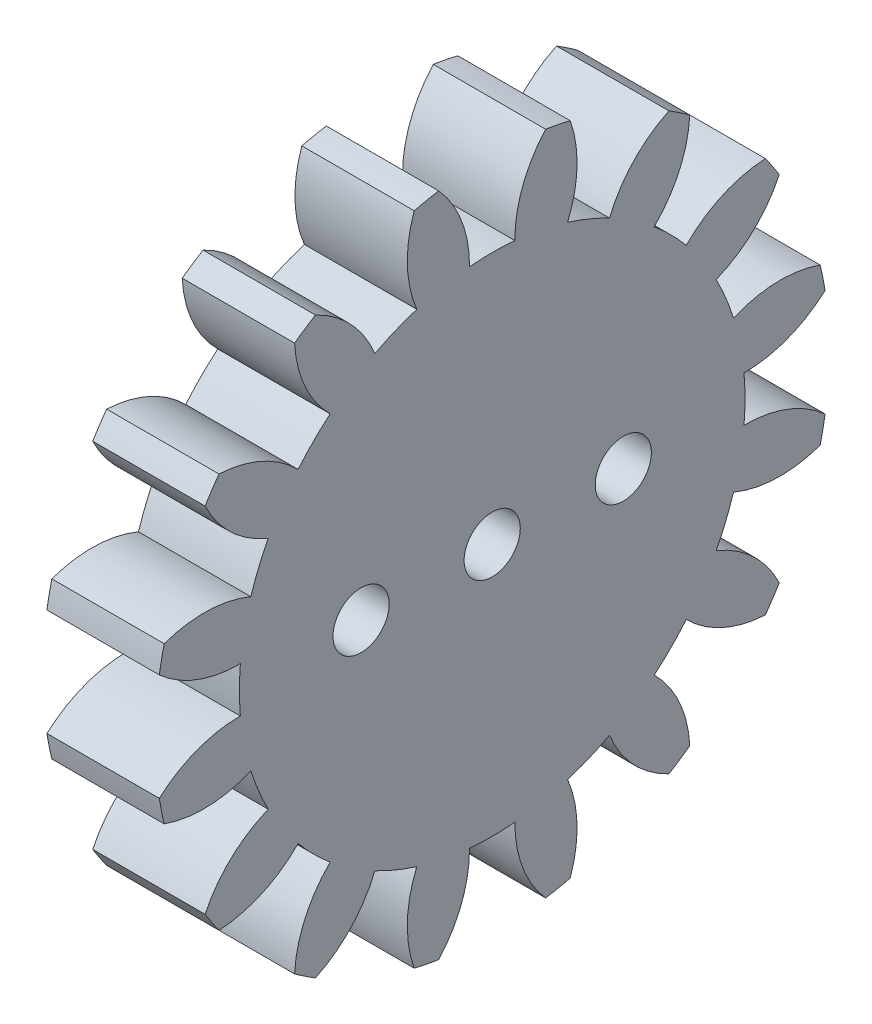
SolidWorks part; units mm, degrees
ref_plane "Plane1" through (0, 0, 0) normal (0, 0, 1) x (1, 0, 0)
ref_plane "Plane2" through (0, 0, 0) normal (0, 1, 0) x (1, 0, 0)
ref_plane "Plane3" through (0, 0, 0) normal (1, 0, 0) x (0, 0, -1)
sketch "HoldingSke" plane through (0, 0, 0) normal (0, 1, 0) x (1, 0, 0)
  line L0 (0, 0) -> (0.4806, -0.1378)
  line L1 (-15, 0) -> (100, 0) construction
  line L2 (0, 0) -> (-2.1039, 2.3779)
  line L3 (0, 0) -> (-11.863, 4.5341)
  line L4 (0, 0) -> (8.3015, 2.3804)
  line L5 (0, 0) -> (-46.8476, -17.4728)
  line L6 (0, 0) -> (-4.9738, -3.3558)
  line L7 (-2.1039, 2.3779) -> (8.6586, 51.2059)
  line L8 (-76.2, 54.61) -> (-74.8, 54.61)
  line L9 (-67.7845, 28.3722) -> (-49.3413, 33.142)
  line L10 (-76.2, 71.12) -> (104.1128, 71.12)
  line L11 (0, 0) -> (-6, 0)
  line L12 (-76.2, 101.6) -> (-76.133, 101.6)
  line L13 (24.9733, 27.94) -> (52.9518, 28.4284)
  line L14 (24.9733, 27.94) -> (24.9743, 27.94)
  line L15 (24.9733, 27.94) -> (100.4006, 29.5858)
  line L16 (-63.627, -2) -> (-12.827, -2)
  circle A0 centre (0, 0) radius 4
  circle A1 centre (0, 0) radius 13.499
  circle A2 centre (0, 0) radius 37.5
  circle A3 centre (0, 0) radius 4
  dimension "MHD" = 26.998
  dimension "Hub_dia" = 75
  dimension "Bore" = 8
  dimension "MBD" = 8
  dimension "Num_teeth" = 16
  dimension "Pitch" = 0.5
  dimension "Overall_len" = 50
  dimension "Show_teeth" = 16
  dimension "Thickness" = 6
  dimension "OAL" = 50.0001
  dimension "T_dim" = 1.4
  dimension "Ap" = 14.5
  dimension "H" = 19.05
  dimension "Pitch_radius" = 180.3128
  dimension "Width" = 6
  dimension "Backlash" = 0.067
  dimension "Addendum_fac" = 1
  dimension "Dedendum_fac" = 1.25
  dimension "Clearance_fac" = 0.25
  dimension "Dedendum_add" = 0.001
  dimension "Module" = 2
sketch "BasProSke" plane through (0, 0, 0) normal (0, 1, 0) x (1, 0, 0)
  line L0 (-10, 0) -> (60, 0) construction
  line L1 (0, 0) -> (0, 18)
  line L2 (0, 0) -> (6, 0)
  line L3 (6, 0) -> (6, 18)
  line L4 (6, 18) -> (0, 18)
  dimension "Thickness" = 6
  dimension "Diameter" = 36
revolve "Base-Revolve" add sketch "BasProSke" angle 360 about L0
sketch "TooCutSke" plane through (0, 0, 0) normal (1, 0, 0) x (0, 0, -1)
  line L1 (0, 0) -> (0, 107) construction
  line L2 (0, 0) -> (-1.6854, 15.911) construction
  line L3 (0, 0) -> (-6.2172, 31.2558) construction
  line L4 (-1.6854, 15.911) -> (-3.1086, 15.6279) construction
  arc A0 (1.2108, 13.4446) -> (-1.2108, 13.4446) centre (0, 0) ccw
  arc A1 (2.8732, 17.7949) -> (-2.8732, 17.7949) centre (0, 0) ccw
  circle A2 centre (0, 0) radius 16 construction
  circle A3 centre (0, 0) radius 15.4904 construction
  arc A4 (-1.2108, 13.4446) -> (-2.8732, 17.7949) centre (-7.6106, 13.4918) ccw
  arc A5 (2.8732, 17.7949) -> (1.2108, 13.4446) centre (7.6106, 13.4918) ccw
  dimension "Root_dia" = 26.998
  dimension "Overcut_dia" = 36.0508
  dimension "Pitch_dia" = 32
  dimension "Base_dia" = 30.9807
  dimension "Flank_rad" = 6.4
  dimension "Half_ang" = 11.25
  dimension "Half_CT" = 1.451
extrude "ToothCut" cut sketch "TooCutSke" along normal through all
fillet "Breaks" [suppressed] radius 0.04
fillet "RootFillets" [suppressed] radius 0.501
pattern_circular "TeethCuts" count 16 every 22.5 about axis through (-10, 0, 0) along (1, 0, 0) of "ToothCut", "RootFillets", "Breaks"
sketch "HubNeaOneSke" plane through (0, 0, 0) normal (-1, 0, 0) x (0, 0, 1)
  circle A0 centre (0, 0) radius 13.499
  dimension "Diameter" = 26.998
extrude "HubNearOne" [suppressed] add sketch "HubNeaOneSke" along normal blind 44.0001
sketch "HubNeaBotSke" plane through (0, 0, 0) normal (-1, 0, 0) x (0, 0, 1)
  circle A0 centre (0, 0) radius 13.499
  dimension "Diameter" = 26.998
extrude "HubNearBoth" [suppressed] add sketch "HubNeaBotSke" along normal blind 22
ref_plane "FarPln" through (6, 0, 0) normal (1, 0, 0) x (0, 0, -1)
sketch "HubFarSke" plane through (6, 0, 0) normal (1, 0, 0) x (0, 0, -1)
  circle A0 centre (0, 0) radius 13.499
  dimension "Diameter" = 26.998
extrude "HubFar" [suppressed] add sketch "HubFarSke" along normal blind 22
sketch "BorSke" plane through (0, 0, 0) normal (1, 0, 0) x (0, 0, -1)
  circle A0 centre (0, 0) radius 4
  dimension "Diameter" = 8
extrude "Bore" cut sketch "BorSke" along normal mid plane 100.0001
sketch "KeySke" plane through (0, 0, 0) normal (1, 0, 0) x (0, 0, -1)
  line L0 (-1.5, 0) -> (-1.5, 5.4)
  line L1 (-1.5, 5.4) -> (1.5, 5.4)
  line L2 (1.5, 5.4) -> (1.5, 0)
  line L3 (0, 0) -> (0, 34) construction
  line L4 (-1.5, 0) -> (1.5, 0)
  dimension "Offset" = 5.4
  dimension "Width" = 3
extrude "Keyway" [suppressed] cut sketch "KeySke" along normal mid plane 100.0001
pattern_circular "Keyway2" [suppressed] count 2 every 90 about axis through (-10, 0, 0) along (1, 0, 0)
sketch "Croquis1" plane through (6, 0, 0) normal (1, 0, 0) x (0, 0, -1)
  circle A0 centre (0, 0) radius 4
  circle A1 centre (0, 0) radius 1.5
extrude "Saliente-Extruir1" add sketch "Croquis1" against normal blind 6
sketch "Croquis2" plane through (6, 0, 0) normal (1, 0, 0) x (0, 0, -1)
  circle A0 centre (-7, 0) radius 1.5
  circle A1 centre (7, 0) radius 1.5
  circle A2 centre (0, 0) radius 1.5 construction
  dimension "D1" = 7
  dimension "D2" = 7
extrude "Cortar-Extruir1" cut sketch "Croquis2" against normal blind 6
equation "' \"Module@HoldingSke\" = 6.35"
equation "' \"Num_teeth@HoldingSke\" = 12"
equation "' \"Ap@HoldingSke\" =  20"
equation "' \"Ap@HoldingSke\" = 20"
equation "' \"Width@HoldingSke\" = 0.5 * 25.4"
equation "' \"Hub_dia@HoldingSke\"= 1 * 25.4"
equation "' \"Hub_dia@HoldingSke\" = 1 * 25.4"
equation "' \"Overall_len@HoldingSke\" = 1.0 * 25.4"
equation "' \"Bore@HoldingSke\" = 0.75 * 25.4"
equation "' \"T_dim@HoldingSke\" = 0.1 * 25.4"
equation "' \"Width@KeySke\" = 0.25 * 25.4"
equation "' \"Show_teeth@HoldingSke\" = 13"
equation "' \"Backlash@HoldingSke\" = 0.009 * 25.4"
equation "' \"Addendum_fac@HoldingSke\" = 1.0"
equation "' \"Dedendum_fac@HoldingSke\" = 1.25"
equation "' \"Dedendum_add@HoldingSke\" = 0.00005 * 25.4"
equation "' \"Clearance_fac@HoldingSke\" = 0.25"
equation "\"Pitch@HoldingSke\" = 1 / \"Module@HoldingSke\""
equation "\"Overcut_dia@TooCutSke\" = (\"Num_teeth@HoldingSke\" + 2 * \"Addendum_fac@HoldingSke\") / \"Pitch@HoldingSke\" + 0.002 * 25.4"
equation "\"Pitch_dia@TooCutSke\" = \"Num_teeth@HoldingSke\" / \"Pitch@HoldingSke\""
equation "\"Base_dia@TooCutSke\" = \"Num_teeth@HoldingSke\" / \"Pitch@HoldingSke\" * cos((\"Ap@HoldingSke\"  * 3.14159265 / 180))"
equation "\"Root_dia@TooCutSke\" = (\"Num_teeth@HoldingSke\" + 2) / \"Pitch@HoldingSke\" - 2 * (\"Addendum_fac@HoldingSke\" + \"Dedendum_fac@HoldingSke\") / \"Pitch@HoldingSke\" - \"Dedendum_add@HoldingSke\" * 2"
equation "\"Half_ang@TooCutSke\" = 180 / \"Num_teeth@HoldingSke\""
equation "\"Half_CT@TooCutSke\" = \"Num_teeth@HoldingSke\" / \"Pitch@HoldingSke\" * sin((3.14159265 / 2 / \"Num_teeth@HoldingSke\")) / 2 - 7 * \"Backlash@HoldingSke\" / 4"
equation "\"Flank_rad@TooCutSke\" = \"Num_teeth@HoldingSke\" / \"Pitch@HoldingSke\" / 5"
equation "\"Radius@RootFillets\" = \"Clearance_fac@HoldingSke\" / \"Pitch@HoldingSke\" + \"Dedendum_add@HoldingSke\""
equation "\"Break_rad@Breaks\" = 0.02 / \"Pitch@HoldingSke\""
equation "\"Thickness@HoldingSke\" = \"Width@HoldingSke\""
equation "\"OAL@HoldingSke\" = \"Thickness@HoldingSke\""
equation "\"MHD@HoldingSke\" = (\"Num_teeth@HoldingSke\" + 2) / \"Pitch@HoldingSke\" - 2 * (\"Addendum_fac@HoldingSke\" + \"Dedendum_fac@HoldingSke\")  / \"Pitch@HoldingSke\" - \"Dedendum_add@HoldingSke\" * 2"
equation "\"MBD@HoldingSke\" = (\"Num_teeth@HoldingSke\" + 2) / \"Pitch@HoldingSke\" - 2 * (\"Addendum_fac@HoldingSke\" + \"Dedendum_fac@HoldingSke\")  / \"Pitch@HoldingSke\" - \"Dedendum_add@HoldingSke\" * 2 - 0.002 * 25.4"
equation "\"MHD@HoldingSke\" = ((sgn( \"MHD@HoldingSke\" - \"Hub_dia@HoldingSke\" )-1)*( \"MHD@HoldingSke\" - \"Hub_dia@HoldingSke\" ))/-2+ \"Hub_dia@HoldingSke\""
equation "\"MBD@HoldingSke\" = ((sgn( \"MBD@HoldingSke\" - \"Bore@HoldingSke\" )-1)*( \"MBD@HoldingSke\" - \"Bore@HoldingSke\" ))/-2+ \"Bore@HoldingSke\""
equation "\"OAL@HoldingSke\" = ((sgn( \"OAL@HoldingSke\" - \"Overall_len@HoldingSke\" )+1)*( \"OAL@HoldingSke\" - \"Overall_len@HoldingSke\" ))/2 + \"Overall_len@HoldingSke\" + 0.000002 * 25.4"
equation "\"Num_teeth@TeethCuts\" = int( \"Show_teeth@HoldingSke\" ) + 1"
equation "\"Num_teeth@TeethCuts\" = ((sgn( \"Num_teeth@TeethCuts\" - \"Num_teeth@HoldingSke\" )-1)*( \"Num_teeth@TeethCuts\" - \"Num_teeth@HoldingSke\" ))/-2+ \"Num_teeth@HoldingSke\""
equation "\"Num_teeth@TeethCuts\" = ((sgn( \"Num_teeth@TeethCuts\" - 2.0)+1)*( \"Num_teeth@TeethCuts\" - 2.0))/2 +2.0"
equation "\"Angle@TeethCuts\" = 360.0 / \"Num_teeth@HoldingSke\""
equation "\"Diameter@BasProSke\" = (\"Num_teeth@HoldingSke\" + 2 * \"Addendum_fac@HoldingSke\") / \"Pitch@HoldingSke\""
equation "\"Thickness@BasProSke\"  = \"Thickness@HoldingSke\""
equation "' \"Fillet_rad@BasProSke\" =  \"Thickness@HoldingSke\" * 0.05"
equation "' \"Fillet_rad@BasProSke\" = \"Thickness@HoldingSke\" * 0.05"
equation "\"MHD@HoldingSke\" = ((sgn( \"MHD@HoldingSke\" - \"Root_dia@TooCutSke\" )-1)*( \"MHD@HoldingSke\" - \"Root_dia@TooCutSke\" ))/-2+ \"Root_dia@TooCutSke\""
equation "\"Diameter@HubNeaOneSke\" = \"MHD@HoldingSke\""
equation "\"Length@HubNearOne\" = \"OAL@HoldingSke\" - \"Thickness@BasProSke\""
equation "\"Diameter@HubNeaBotSke\" = \"MHD@HoldingSke\""
equation "\"Length@HubNearBoth\" = ( \"OAL@HoldingSke\" - \"Thickness@BasProSke\" ) / 2.0"
equation "\"Thickness@FarPln\" = \"Thickness@BasProSke\""
equation "\"Diameter@HubFarSke\" = \"MHD@HoldingSke\""
equation "\"Length@HubFar\" = ( \"OAL@HoldingSke\" - \"Thickness@BasProSke\" ) / 2.0"
equation "\"Diameter@BorSke\" = \"MBD@HoldingSke\""
equation "\"D1@Bore\" = \"OAL@HoldingSke\" * 2.0"
equation "\"D1@Keyway\" = \"OAL@HoldingSke\" * 2.0"
equation "\"Offset@KeySke\" = \"T_dim@HoldingSke\" + \"MBD@HoldingSke\" / 2.0"
